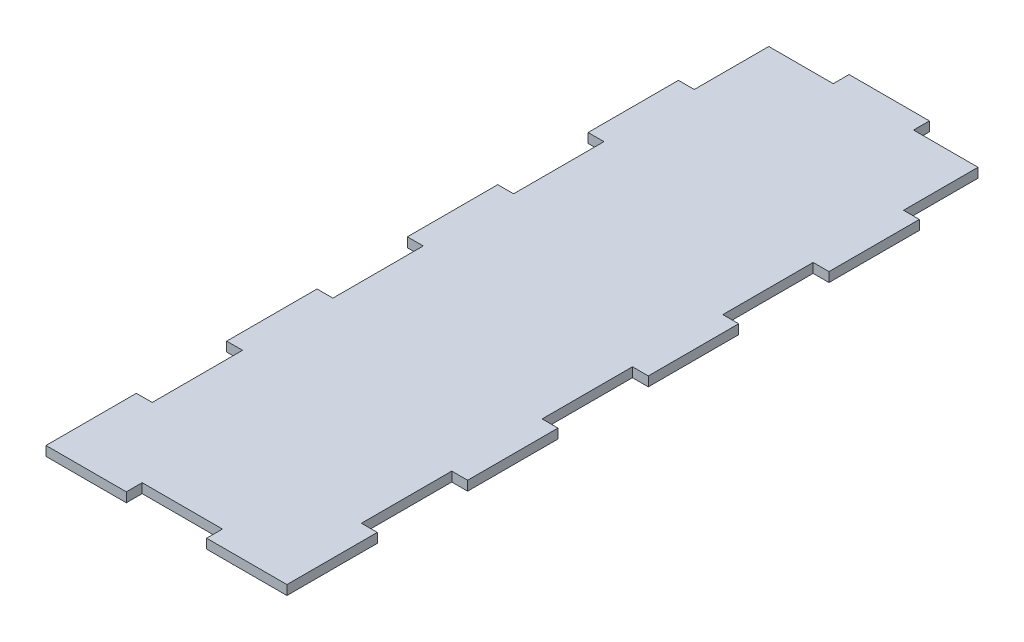
SolidWorks part; units mm, degrees
ref_plane "Front Plane" through (0, 0, 0) normal (0, 0, 1) x (1, 0, 0)
ref_plane "Top Plane" through (0, 0, 0) normal (0, 1, 0) x (1, 0, 0)
ref_plane "Right Plane" through (0, 0, 0) normal (1, 0, 0) x (0, 0, -1)
sketch "Sketch1" plane through (0, 0, 0) normal (0, 1, 0) x (1, 0, 0)
  line L0 (-38, -114) -> (-12.6667, -114)
  line L1 (-38, -114) -> (38, -114) construction
  line L2 (-38, -114) -> (-38, 114) construction
  line L3 (-38, 114) -> (38, 114) construction
  line L4 (38, -114) -> (38, 114) construction
  line L5 (0, 114) -> (0, -114) construction
  line L6 (-38, 0) -> (38, 0) construction
  line L7 (-12.6667, -114) -> (-12.6667, -109)
  line L8 (-12.6667, -109) -> (0, -109)
  line L9 (-38, -114) -> (-38, -85.5)
  line L13 (-38, -85.5) -> (-33, -85.5)
  line L14 (-33, -85.5) -> (-33, -57)
  line L15 (-33, -57) -> (-38, -57)
  line L20 (0, -109) -> (0, 114)
  line L22 (-33, 109) -> (-33, 85.5)
  line L23 (-33, 109) -> (-12.6667, 109)
  line L24 (-38, -57) -> (-38, -28.5)
  line L25 (-38, -28.5) -> (-33, -28.5)
  line L26 (-33, -28.5) -> (-33, 0)
  line L27 (-33, 0) -> (-38, 0)
  line L28 (-38, 0) -> (-38, 28.5)
  line L29 (-38, 28.5) -> (-33, 28.5)
  line L30 (-33, 28.5) -> (-33, 57)
  line L31 (-33, 57) -> (-38, 57)
  line L32 (-38, 57) -> (-38, 85.5)
  line L33 (-38, 85.5) -> (-33, 85.5)
  line L34 (-12.6667, 109) -> (-12.6667, 114)
  line L35 (-12.6667, 114) -> (0, 114)
  point P12 (0, 0)
  point P56 (0, 0)
  dimension "D1" = 228
  dimension "D2" = 76
  dimension "D4" = 5
  dimension "D6" = 5
  dimension "D5" = 28.5
  dimension "D8" = 28.5
  dimension "D9" = 28.5
  dimension "D10" = 28.5
  dimension "D11" = 28.5
  dimension "D12" = 28.5
  dimension "D3" = 12.6667
  dimension "D7" = 5
  dimension "D13" = 28.5
extrude "Boss-Extrude1" add sketch "Sketch1" along normal blind 3
mirror "Mirror1" about plane through (0, 3, 109) normal (-1, 0, 0) of "Boss-Extrude1"
equation "\"3mm akryyli\"= 3mm"
equation "\"5mm akryyli\"= 5mm"
equation "\"D4@Sketch1\"=\"5mm akryyli\""
equation "\"D6@Sketch1\"=\"5mm akryyli\""
equation "\"D7@Sketch1\"=\"5mm akryyli\""
